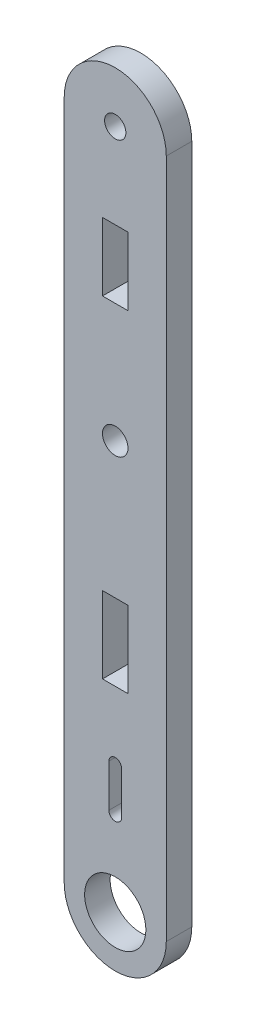
SolidWorks part; units mm, degrees
ref_plane "前基準面" through (0, 0, 0) normal (0, 0, 1) x (1, 0, 0)
ref_plane "上基準面" through (0, 0, 0) normal (0, 1, 0) x (1, 0, 0)
ref_plane "右基準面" through (0, 0, 0) normal (1, 0, 0) x (0, 0, -1)
sketch "草圖3" plane through (0, 0, 0) normal (0, 0, 1) x (1, 0, 0)
  line L0 (6.3003, 18.2999) -> (6.3003, 23.2999) construction
  line L1 (5.5503, 18.2999) -> (5.5503, 23.2999)
  line L2 (7.0503, 18.2999) -> (7.0503, 23.2999)
  line L3 (0.3003, 88.3) -> (0.3003, 8.2999)
  line L4 (4.8003, 78.2999) -> (7.8003, 78.2999)
  line L5 (4.8003, 78.2999) -> (4.8003, 70.2999)
  line L6 (4.8003, 70.2999) -> (7.8003, 70.2999)
  line L7 (7.8003, 78.2999) -> (7.8003, 70.2999)
  line L8 (7.8003, 31.2999) -> (4.8003, 31.2999)
  line L9 (7.8003, 31.2999) -> (7.8003, 40.2999)
  line L10 (7.8003, 40.2999) -> (4.8003, 40.2999)
  line L11 (4.8003, 31.2999) -> (4.8003, 40.2999)
  line L12 (12.3003, 8.2999) -> (12.3003, 88.2999)
  circle A0 centre (6.3003, 8.2999) radius 3.6
  circle A1 centre (6.3003, 8.2999) radius 3.6 construction
  arc A2 (5.5503, 18.2999) -> (7.0503, 18.2999) centre (6.3003, 18.2999) ccw
  arc A3 (7.0503, 23.2999) -> (5.5503, 23.2999) centre (6.3003, 23.2999) ccw
  arc A4 (0.3003, 8.2999) -> (12.3003, 8.2999) centre (6.3003, 8.2999) ccw
  arc A5 (0.3003, 8.2999) -> (12.3003, 8.2999) centre (6.3003, 8.2999) ccw construction
  circle A6 centre (6.3003, 56.3) radius 1.5
  circle A7 centre (6.3003, 56.3) radius 1.5 construction
  circle A8 centre (6.3003, 88.2999) radius 1.25
  circle A9 centre (6.3003, 88.2999) radius 1.25 construction
  arc A10 (0.3003, 88.3) -> (12.3003, 88.2999) centre (6.3003, 88.2999) cw
  arc A11 (6.8038, 94.2788) -> (0.3003, 88.3) centre (6.3003, 88.2999) ccw construction
  point P9 (6.3003, 20.7999)
extrude "填料-伸長1" add sketch "草圖3" along normal blind 3
